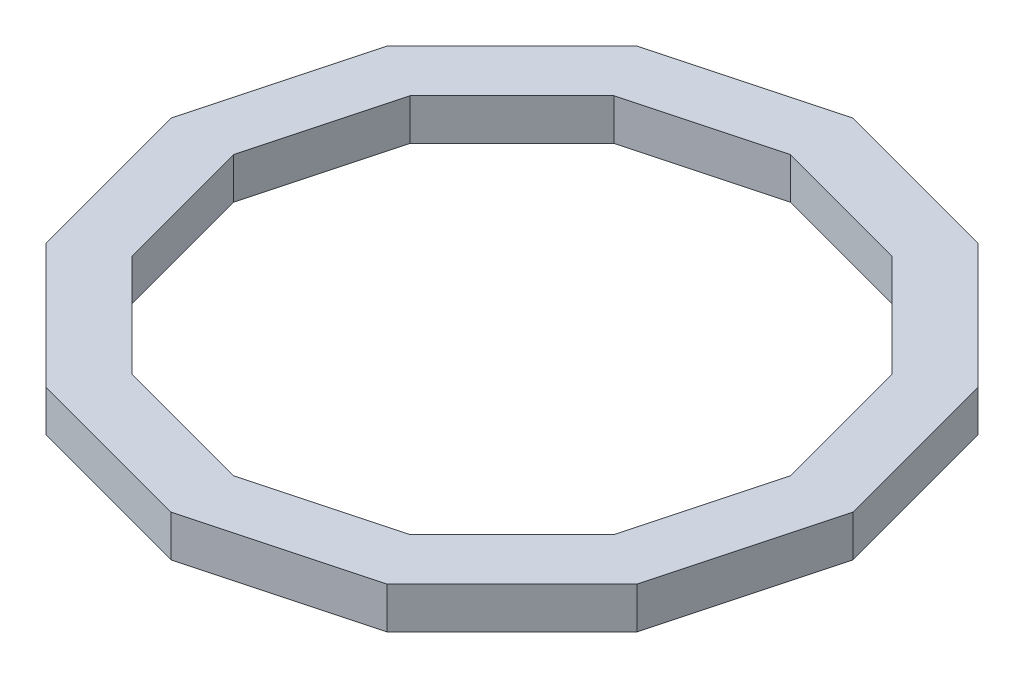
SolidWorks part; units mm, degrees
ref_plane "Front Plane" through (0, 0, 0) normal (0, 0, 1) x (1, 0, 0)
ref_plane "Top Plane" through (0, 0, 0) normal (0, 1, 0) x (1, 0, 0)
ref_plane "Right Plane" through (0, 0, 0) normal (1, 0, 0) x (0, 0, -1)
sketch "Sketch2" plane through (0, 0, 0) normal (0, 1, 0) x (1, 0, 0)
  line L0 (0, 0) -> (-128.0953, 0) construction
  line L1 (-157.0209, 0) -> (-135.9841, -78.5105)
  line L2 (-135.9841, -78.5105) -> (-78.5105, -135.9841)
  line L3 (-78.5105, -135.9841) -> (0, -157.0209)
  line L4 (0, -157.0209) -> (78.5105, -135.9841)
  line L5 (78.5105, -135.9841) -> (135.9841, -78.5105)
  line L6 (135.9841, -78.5105) -> (157.0209, 0)
  line L7 (157.0209, 0) -> (135.9841, 78.5105)
  line L8 (135.9841, 78.5105) -> (78.5105, 135.9841)
  line L9 (78.5105, 135.9841) -> (0, 157.0209)
  line L10 (0, 157.0209) -> (-78.5105, 135.9841)
  line L11 (-78.5105, 135.9841) -> (-135.9841, 78.5105)
  line L12 (-135.9841, 78.5105) -> (-157.0209, 0)
  line L13 (-128.0953, 0) -> (-110.9338, -64.0476)
  line L14 (-110.9338, -64.0476) -> (-64.0476, -110.9338)
  line L15 (-64.0476, -110.9338) -> (0, -128.0953)
  line L16 (0, -128.0953) -> (64.0476, -110.9338)
  line L17 (64.0476, -110.9338) -> (110.9338, -64.0476)
  line L18 (110.9338, -64.0476) -> (128.0953, 0)
  line L19 (128.0953, 0) -> (110.9338, 64.0476)
  line L20 (110.9338, 64.0476) -> (64.0476, 110.9338)
  line L21 (64.0476, 110.9338) -> (0, 128.0953)
  line L22 (0, 128.0953) -> (-64.0476, 110.9338)
  line L23 (-64.0476, 110.9338) -> (-110.9338, 64.0476)
  line L24 (-110.9338, 64.0476) -> (-128.0953, 0)
  line L25 (-157.0209, 0) -> (-128.0953, 0) construction
  circle A0 centre (0, 0) radius 151.6705 construction
  circle A1 centre (0, 0) radius 123.7305 construction
  dimension "D1" = 81.28
  dimension "D2" = 27.94
extrude "Boss-Extrude2" add sketch "Sketch2" along normal blind 19.05
